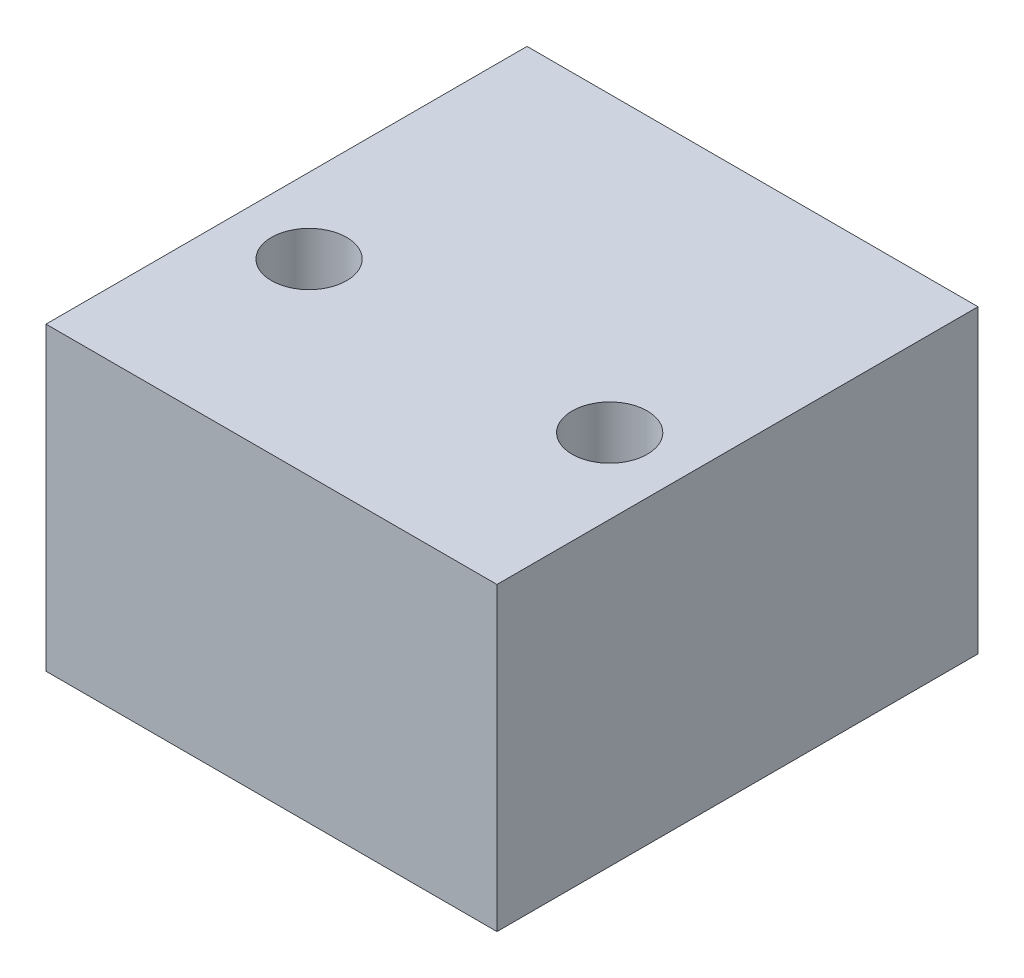
SolidWorks part; units mm, degrees
ref_plane "Front Plane" through (0, 0, 0) normal (0, 0, 1) x (1, 0, 0)
ref_plane "Top Plane" through (0, 0, 0) normal (0, 1, 0) x (1, 0, 0)
ref_plane "Right Plane" through (0, 0, 0) normal (1, 0, 0) x (0, 0, -1)
sketch "Sketch1" plane through (0, 0, 0) normal (0, 1, 0) x (1, 0, 0)
  line L0 (-12.5, -2.5) -> (-12.5, 2.5) construction
  line L1 (-15, 14.5) -> (15, 14.5) construction
  line L2 (-15, 14.5) -> (-15, -7.5) construction
  line L3 (-15, -7.5) -> (15, -7.5) construction
  line L4 (15, 14.5) -> (15, -7.5) construction
  line L5 (-7.5, -2.5) -> (-7.5, 2.5) construction
  line L6 (7.5, -2.5) -> (7.5, 2.5) construction
  line L7 (12.5, -2.5) -> (12.5, 2.5) construction
  line L8 (-10, 5) -> (-10, 2.5) construction
  line L9 (-10, 2.5) -> (-10, -2.5) construction
  line L10 (-10, -2.5) -> (-10, -5) construction
  line L11 (-10, 0) -> (-7.5, 0) construction
  line L12 (-7.5, 0) -> (0, 0) construction
  line L13 (0, 0) -> (7.5, 0) construction
  line L14 (-10, 2.5) -> (10, 2.5) construction
  line L15 (-15, 7.5) -> (15, 7.5) construction
  line L16 (-10, -2.5) -> (10, -2.5) construction
  line L17 (0, 0) -> (0, -7.5) construction
  line L18 (0, 0) -> (0, 7.5) construction
  line L20 (-15, 19.5) -> (15, 19.5)
  line L21 (-15, 19.5) -> (-15, -12.5)
  line L22 (-15, -12.5) -> (15, -12.5)
  line L23 (15, 19.5) -> (15, -12.5)
  circle A0 centre (-10, 2.5) radius 2.5 construction
  circle A1 centre (-10, -2.5) radius 2.5 construction
  circle A2 centre (10, 2.5) radius 2.5 construction
  circle A3 centre (10, -2.5) radius 2.5 construction
  circle A4 centre (-10, 0) radius 2.5
  circle A5 centre (10, 0) radius 2.5
  dimension "D1" = 22
  dimension "D2" = 30
  dimension "D3" = 7
  dimension "D4" = 15
  dimension "D5" = 5
  dimension "D6" = 10
  dimension "D7" = 5
  dimension "D8" = 5
extrude "Boss-Extrude1" add sketch "Sketch1" along normal blind 20 contours L4 L1 L2 L3 A3 L6 A2 L7 A1 L0 A0 L5 | L23 L20 L21 L22 A5 A4
